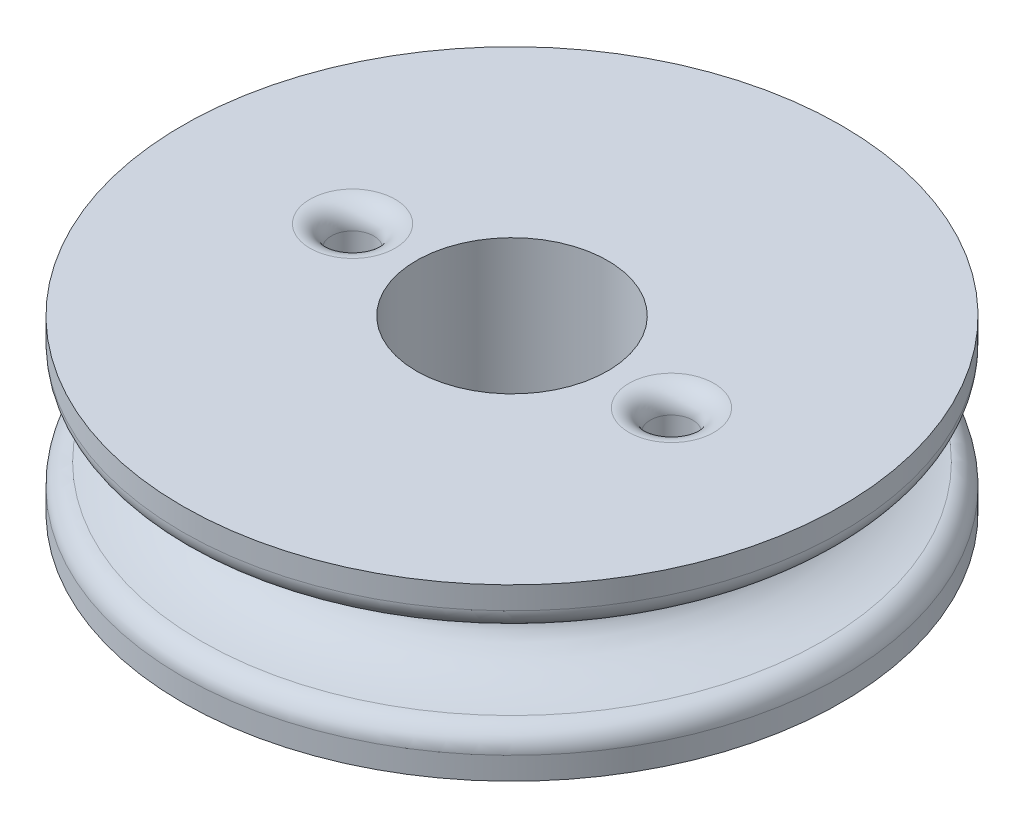
SolidWorks part; units mm, degrees
ref_plane "Front Plane" through (0, 0, 0) normal (0, 0, 1) x (1, 0, 0)
ref_plane "Top Plane" through (0, 0, 0) normal (0, 1, 0) x (1, 0, 0)
ref_plane "Right Plane" through (0, 0, 0) normal (1, 0, 0) x (0, 0, -1)
sketch "Sketch2" plane through (0, 0, 0) normal (0, 1, 0) x (1, 0, 0)
  line L0 (-22.2195, 0) -> (25.3848, 0) construction
  line L1 (0, 17.6266) -> (0, -23.0263) construction
  circle A0 centre (0, 0) radius 15.5
  circle A1 centre (0, 0) radius 4.5
  circle A2 centre (7.5, 0) radius 1
  circle A3 centre (-7.5, 0) radius 1
  dimension "D1" = 31
  dimension "D2" = 9
  dimension "D3" = 7.5
  dimension "D4" = 2
extrude "Boss-Extrude1" add sketch "Sketch2" along normal blind 8
fillet "Fillet1" radius 1 2 edges at (7.5, 8, 1) (-7.5, 8, -1)
sketch "Sketch4" plane through (0, 0, 0) normal (0, 0, 1) x (1, 0, 0)
  line L0 (0, 9.6047) -> (0, -4.1687) construction
  line L1 (-18.3835, 4) -> (17.1949, 4) construction
  line L2 (-15.5, 8) -> (-15.5, 0) construction
  arc A0 (-15.5, 6) -> (-15.5, 2) centre (-15.5, 4) ccw
  ellipse E0 centre (-15.5, 4) end of major axis (-11.5, 4) minor radius 2 (-15.5, 2) -> (-15.5, 6) ccw
  dimension "D1" = 4
  dimension "D2" = 4
revolve "Cut-Revolve1" cut sketch "Sketch4" angle 360 about L0
fillet "Fillet2" radius 1 2 edges at (0, 6, 15.5) (0, 2, 15.5)
